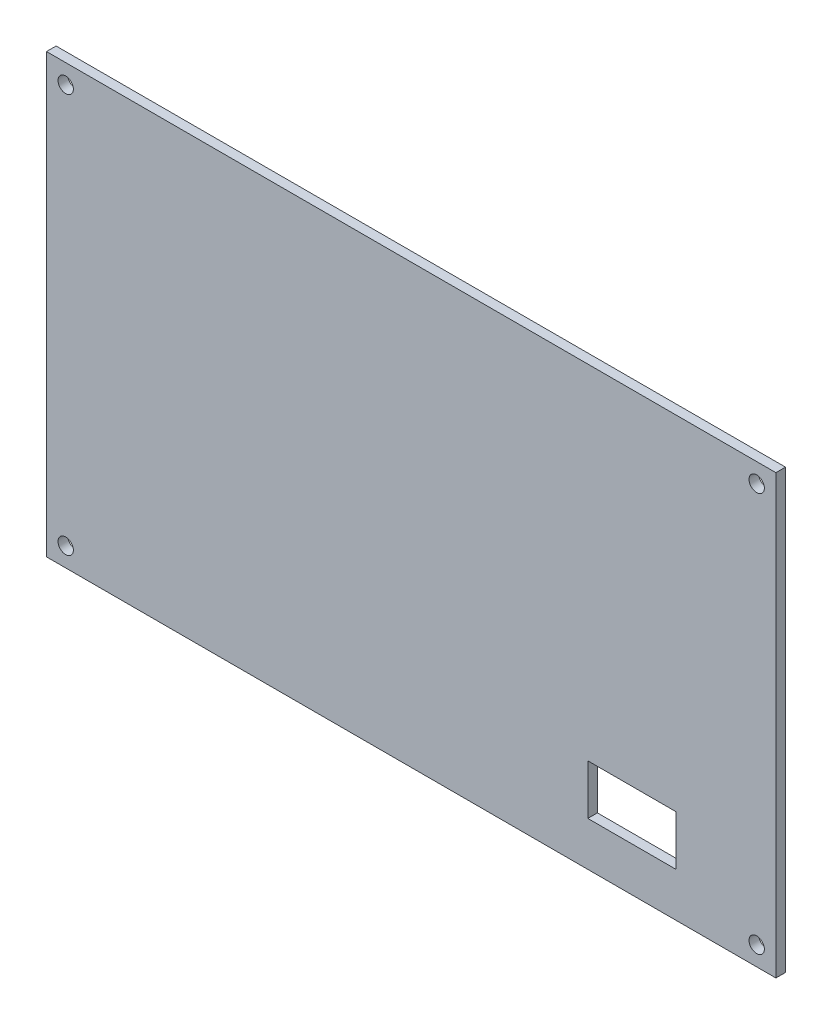
SolidWorks part; units mm, degrees
ref_plane "Front Plane" through (0, 0, 0) normal (0, 0, 1) x (1, 0, 0)
ref_plane "Top Plane" through (0, 0, 0) normal (0, 1, 0) x (1, 0, 0)
ref_plane "Right Plane" through (0, 0, 0) normal (1, 0, 0) x (0, 0, -1)
sketch "Sketch1" plane through (0, 0, 0) normal (0, 0, 1) x (1, 0, 0)
  line L1 (-95, -57) -> (95, -57)
  line L2 (-95, -57) -> (-95, 57)
  line L3 (-95, 57) -> (95, 57)
  line L4 (95, -57) -> (95, 57)
  line L5 (-95, -57) -> (95, 57) construction
  line L6 (-95, 57) -> (95, -57) construction
  point P0 (0, 0)
  dimension "D1" = 190
  dimension "D2" = 114
extrude "Boss-Extrude1" add sketch "Sketch1" along normal blind 2.5
sketch "Sketch2" plane through (0, 0, 2.5) normal (0, 0, 1) x (1, 0, 0)
  text T0 "RIGHT" font "Century Gothic" height in points 72
extrude "Cut-Extrude1" [suppressed] cut sketch "Sketch2" against normal blind 1
sketch "Sketch3" plane through (0, 0, 2.5) normal (0, 0, 1) x (1, 0, 0)
  line L0 (-95, 57) -> (-95, -57) construction
  line L1 (95, 57) -> (-95, 57) construction
  line L2 (95, -57) -> (95, 57) construction
  line L3 (-95, -57) -> (95, -57) construction
  circle A0 centre (-90, 52) radius 2
  circle A1 centre (90, 52) radius 2
  circle A2 centre (90, -52) radius 2
  circle A3 centre (-90, -52) radius 2
  dimension "D1" = 4
  dimension "D2" = 5
  dimension "D3" = 5
  dimension "D6" = 5
  dimension "D7" = 5
  dimension "D4" = 2
  dimension "D5" = 2
extrude "Cut-Extrude2" cut sketch "Sketch3" against normal blind 10
sketch "Sketch4" plane through (0, 0, 2.5) normal (0, 0, 1) x (1, 0, 0)
  line L1 (46, -45.5) -> (69, -45.5)
  line L2 (46, -45.5) -> (46, -32.5)
  line L3 (46, -32.5) -> (69, -32.5)
  line L4 (69, -45.5) -> (69, -32.5)
  line L5 (46, -45.5) -> (69, -32.5) construction
  line L6 (46, -32.5) -> (69, -45.5) construction
  line L7 (95, 57) -> (-95, 57) construction
  line L8 (95, -57) -> (95, 57) construction
  point P0 (57.5, -39)
  dimension "D1" = 26
  dimension "D2" = 23
  dimension "D3" = 89.5
  dimension "D4" = 13
extrude "Cut-Extrude3" cut sketch "Sketch4" against normal blind 21
